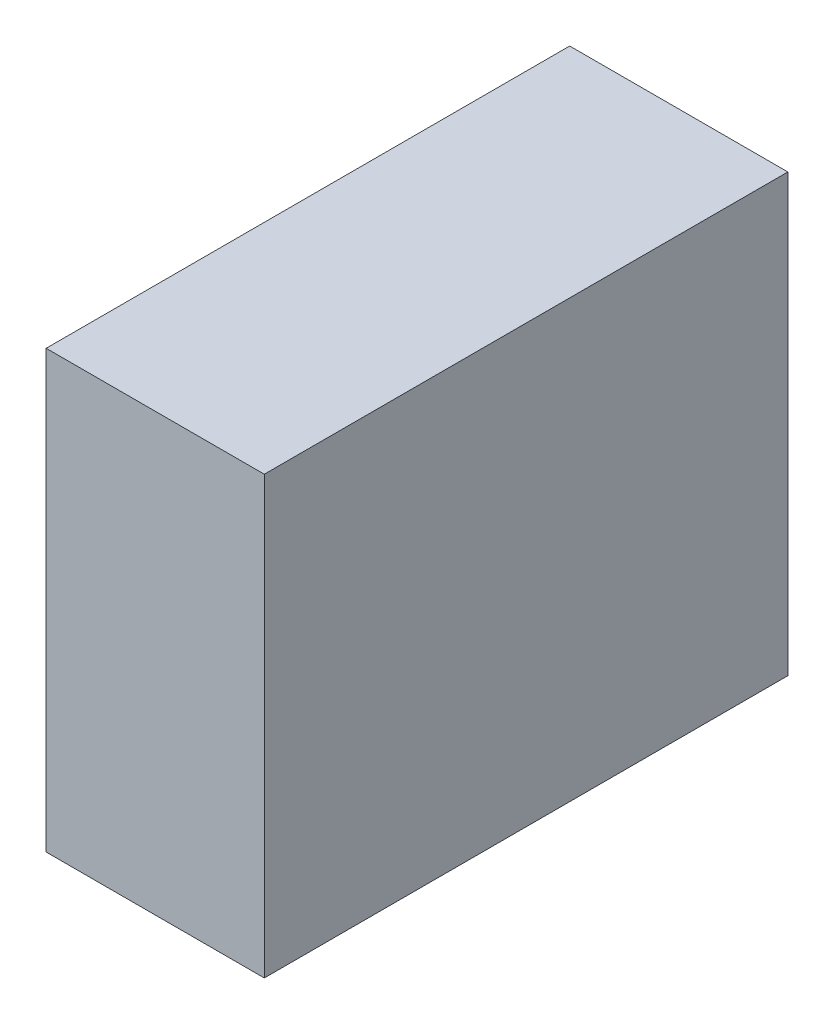
SolidWorks part; units mm, degrees
ref_plane "Front Plane" through (0, 0, 0) normal (0, 0, 1) x (1, 0, 0)
ref_plane "Top Plane" through (0, 0, 0) normal (0, 1, 0) x (1, 0, 0)
ref_plane "Right Plane" through (0, 0, 0) normal (1, 0, 0) x (0, 0, -1)
other "Configuration Table"
sketch "Sketch1" plane through (0, 0, 0) normal (0, 0, 1) x (1, 0, 0)
  line L1 (440, 200) -> (490, 200)
  line L2 (440, 200) -> (440, 300)
  line L3 (440, 300) -> (490, 300)
  line L4 (490, 200) -> (490, 300)
extrude "OVEN_pano_surucu_pres_1" add sketch "Sketch1" against normal blind 120 from offset 128 separate body
